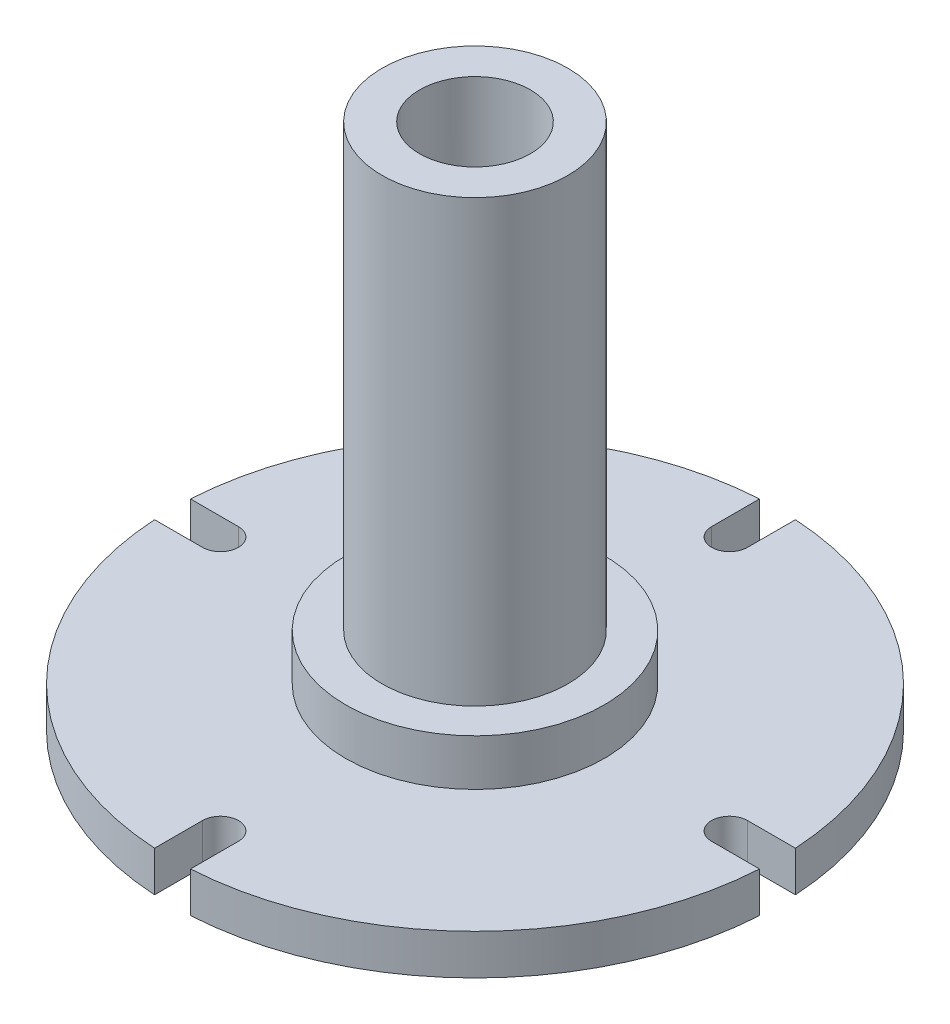
SolidWorks part; units mm, degrees
ref_plane "Front Plane" through (0, 0, 0) normal (0, 0, 1) x (1, 0, 0)
ref_plane "Top Plane" through (0, 0, 0) normal (0, 1, 0) x (1, 0, 0)
ref_plane "Right Plane" through (0, 0, 0) normal (1, 0, 0) x (0, 0, -1)
sketch "Sketch2" plane through (0, 0, 0) normal (0, 0, 1) x (1, 0, 0)
  line L0 (0, 0) -> (37.5, 0)
  line L1 (37.5, 0) -> (37.5, 5)
  line L2 (37.5, 5) -> (16, 5)
  line L3 (16, 5) -> (16, 10.75)
  line L4 (16, 10.75) -> (0, 10.75)
  line L5 (0, 10.75) -> (0, 0) construction
  line L6 (0, 0) -> (0, 10.75)
  dimension "D1" = 75
  dimension "D2" = 5
  dimension "D3" = 32
  dimension "D4" = 5.75
revolve "Revolve1" add sketch "Sketch2" angle 360 about L5
hole_wizard "1/4 NPT Tapped Hole1" positions "Sketch3" profile "Sketch4" size "1/4" standard "ANSI Inch" end condition through all
sketch "Sketch3" plane through (0, 0, 0) normal (0, -1, 0) x (-1, 0, 0)
  point P0 (0, 0)
sketch "Sketch4" plane through (0, 0, 0) normal (1, 0, 0) x (0, 0, -1)
  line L0 (0, 0) -> (0, 10.75)
  line L1 (0, 10.75) -> (5.5626, 10.75)
  line L2 (-6.558, 10.0203) -> (-6.858, 0) construction
  line L3 (5.5626, 10.75) -> (5.5626, 10.0203)
  line L4 (5.5626, 10.0203) -> (6.558, 10.0203)
  line L5 (6.558, 10.0203) -> (6.858, 0)
  line L7 (6.858, 0) -> (0, 0)
  line L8 (0, -6.35) -> (0, 107.95) construction
  line L11 (-5.5626, 10.0203) -> (-6.558, 10.0203) construction
  dimension "Thru Tap Drill Dia." = 11.1252
  dimension "Thru Tap Drill Depth" = 10.75
  dimension "Thread Dia." = 13.716
  dimension "Thread Angle" = 3.43
  dimension "Thread Depth" = 10.0203
sketch "Sketch5" plane through (0, 5, 0) normal (0, 1, 0) x (1, 0, 0)
  line L0 (0, 37.5) -> (0, 31.5) construction
  line L1 (2.225, 37.5) -> (2.225, 31.5)
  line L2 (-2.225, 37.5) -> (-2.225, 31.5)
  circle A0 centre (0, 0) radius 37.5 construction
  arc A1 (2.225, 37.5) -> (-2.225, 37.5) centre (0, 37.5) ccw
  arc A2 (-2.225, 31.5) -> (2.225, 31.5) centre (0, 31.5) ccw
  point P6 (0, 34.5)
  dimension "D1" = 31.5
  dimension "D2" = 4.45
extrude "Cut-Extrude1" cut sketch "Sketch5" against normal through all
pattern_circular "CirPattern1" count 4 over 360 about axis through (0, 0, 0) along (0, 1, 0) of "Cut-Extrude1"
sketch "Sketch6" plane through (0, 0, 0) normal (0, -1, 0) x (1, 0, 0)
  circle A0 centre (0, 0) radius 11.5
  dimension "D1" = 23
split line "Split Line1"
sketch "Sketch7" plane through (0, 0, 0) normal (0, -1, 0) x (1, 0, 0)
  line L0 (0, 31.5) -> (0, -31.5) construction
  line L1 (11.75, 0) -> (-11.75, 0) construction
  line L2 (-11.75, 1.3) -> (-11.75, -1.3) construction
  line L3 (-11.75, 1.3) -> (-11.75, 3.9) construction
  line L4 (-11.75, 3.9) -> (-11.75, 6.5) construction
  line L5 (-11.75, -1.3) -> (-11.75, -3.9) construction
  line L6 (-11.75, -3.9) -> (-11.75, -6.5) construction
  circle A0 centre (-11.75, 6.5) radius 0.5
  circle A1 centre (-11.75, 3.9) radius 0.5
  circle A2 centre (-11.75, 1.3) radius 0.5
  circle A3 centre (-11.75, -1.3) radius 0.5
  circle A4 centre (-11.75, -3.9) radius 0.5
  circle A5 centre (-11.75, -6.5) radius 0.5
  circle A6 centre (11.75, -6.5) radius 0.5
  circle A7 centre (11.75, -3.9) radius 0.5
  circle A8 centre (11.75, -1.3) radius 0.5
  circle A9 centre (11.75, 1.3) radius 0.5
  circle A10 centre (11.75, 3.9) radius 0.5
  circle A11 centre (11.75, 6.5) radius 0.5
  point P7 (0, 0)
  point P11 (0, 0)
  dimension "D1" = 1
  dimension "D2" = 23.5
  dimension "D3" = 13
extrude "Boss-Extrude1" add sketch "Sketch7" along normal blind 12 separate body
sketch "Sketch8" plane through (0, 10.75, 0) normal (0, -1, 0) x (1, 0, 0)
  circle A0 centre (0, 0) radius 6.858 construction
  circle A1 centre (0, 0) radius 11.5
  circle A2 centre (0, 0) radius 11.5
  circle A3 centre (0, 0) radius 6.858
  dimension "D1" = 0
extrude "Boss-Extrude3" add sketch "Sketch8" against normal blind 54.5 separate body
sketch "Sketch9" plane through (0, 10.75, 0) normal (0, 1, 0) x (1, 0, 0)
  circle A0 centre (0, 0) radius 5
  circle A1 centre (0, 0) radius 6.858 construction
  circle A2 centre (0, 0) radius 6.858
  dimension "D1" = 10
extrude "Boss-Extrude4" add sketch "Sketch9" along normal blind 40.64
